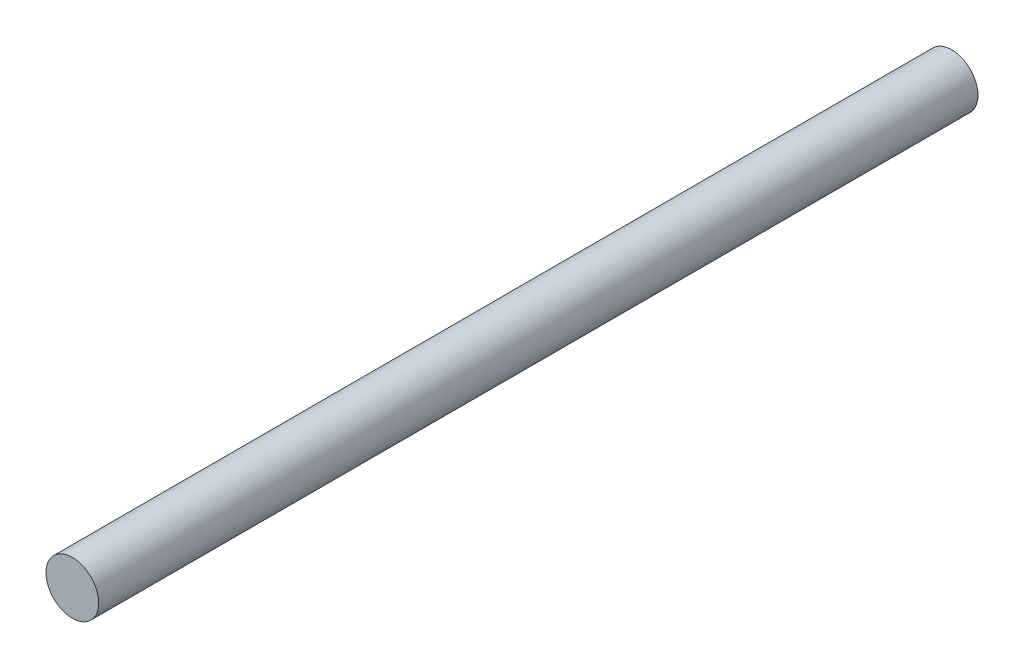
SolidWorks part; units mm, degrees
ref_plane "Front Plane" through (0, 0, 0) normal (0, 0, 1) x (1, 0, 0)
ref_plane "Top Plane" through (0, 0, 0) normal (0, 1, 0) x (1, 0, 0)
ref_plane "Right Plane" through (0, 0, 0) normal (1, 0, 0) x (0, 0, -1)
sketch "Sketch1" plane through (0, 0, 0) normal (0, 0, 1) x (1, 0, 0)
  circle A0 centre (0, 0) radius 30
extrude "Boss-Extrude1" add sketch "Sketch1" along normal blind 1000
